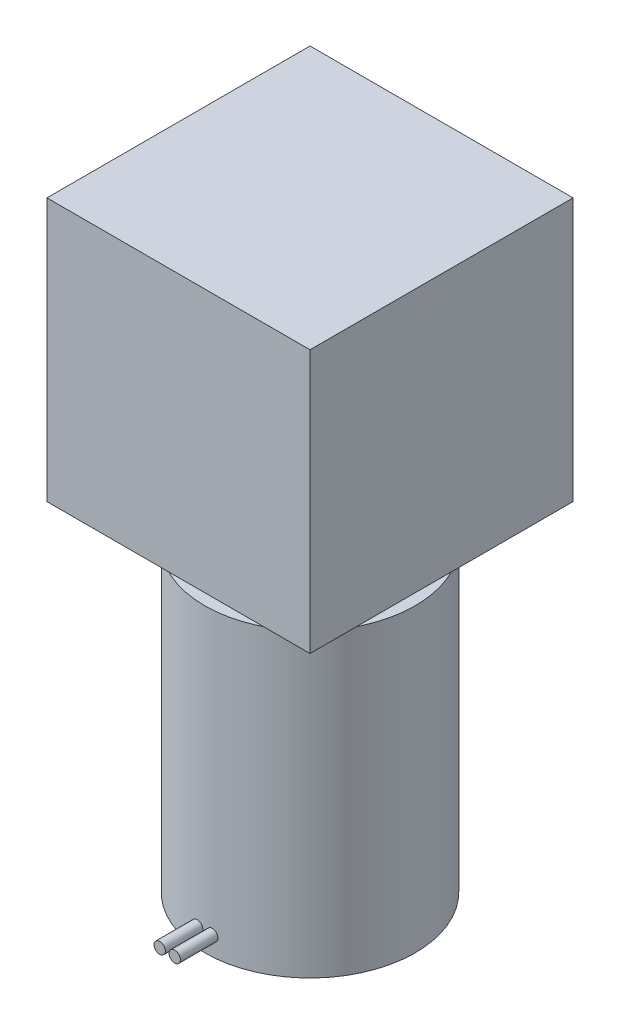
SolidWorks part; units mm, degrees
ref_plane "Front Plane" through (0, 0, 0) normal (0, 0, 1) x (1, 0, 0)
ref_plane "Top Plane" through (0, 0, 0) normal (0, 1, 0) x (1, 0, 0)
ref_plane "Right Plane" through (0, 0, 0) normal (1, 0, 0) x (0, 0, -1)
sketch "Sketch1" plane through (0, 0, 0) normal (0, 1, 0) x (1, 0, 0)
  circle A0 centre (0, 0) radius 28
  dimension "D1" = 56
extrude "Boss-Extrude1" add sketch "Sketch1" along normal blind 80
sketch "Sketch3" plane through (0, 80, 0) normal (0, 1, 0) x (1, 0, 0)
  circle A0 centre (0, 0) radius 22.5
  dimension "D1" = 45
extrude "Boss-Extrude2" add sketch "Sketch3" along normal blind 10
sketch "Sketch4" plane through (0, 90, 0) normal (0, 1, 0) x (1, 0, 0)
  line L1 (-35, 35) -> (35, 35)
  line L2 (-35, 35) -> (-35, -35)
  line L3 (-35, -35) -> (35, -35)
  line L4 (35, 35) -> (35, -35)
  line L5 (-35, 35) -> (35, -35) construction
  line L6 (-35, -35) -> (35, 35) construction
  point P0 (0, 0)
  dimension "D1" = 70
  dimension "D2" = 70
extrude "Boss-Extrude3" add sketch "Sketch4" along normal blind 70
sketch "Sketch5" plane through (-35, 0, 0) normal (-1, 0, 0) x (0, 0, 1)
  circle A0 centre (0, 125) radius 5.5
  circle A1 centre (0, 152) radius 2.5
  circle A2 centre (19.0919, 144.0919) radius 2.5
  circle A3 centre (27, 125) radius 2.5
  circle A4 centre (19.0919, 105.9081) radius 2.5
  circle A5 centre (0, 98) radius 2.5
  circle A6 centre (-19.0919, 105.9081) radius 2.5
  circle A7 centre (-27, 125) radius 2.5
  circle A8 centre (-19.0919, 144.0919) radius 2.5
  point P20 (0, 125)
  dimension "D1" = 11
  dimension "D2" = 5
  dimension "D3" = 27
  dimension "D4" = 8
extrude "Cut-Extrude1" cut sketch "Sketch5" against normal blind 20
ref_plane "Plane2" through (0, 0, 28) normal (0, 0, 1) x (1, 0, 0)
sketch "Sketch6" plane through (0, 0, 28) normal (0, 0, 1) x (1, 0, 0)
  circle A0 centre (-2, 5.1539) radius 1.5
  circle A1 centre (2, 5.1539) radius 1.5
  dimension "D1" = 3
  dimension "D2" = 3
  dimension "D3" = 4
  dimension "D4" = 2
extrude "Boss-Extrude4" add sketch "Sketch6" along normal blind 10 separate body
sketch "Sketch7" plane through (-35, 0, 0) normal (-1, 0, 0) x (0, 0, 1)
  line L1 (-6.5, 126.5) -> (-4.5, 126.5)
  line L2 (-6.5, 126.5) -> (-6.5, 123.5)
  line L3 (-6.5, 123.5) -> (-4.5, 123.5)
  line L4 (-4.5, 126.5) -> (-4.5, 123.5)
  line L5 (-6.5, 126.5) -> (-4.5, 123.5) construction
  line L6 (-6.5, 123.5) -> (-4.5, 126.5) construction
  circle A0 centre (0, 125) radius 5.5 construction
  circle A1 centre (0, 125) radius 5.5 construction
  point P0 (-5.5, 125)
  dimension "D2" = 3
  dimension "D1" = 2
extrude "Cut-Extrude2" cut sketch "Sketch7" against normal blind 20
sketch "Sketch8" plane through (-35, 0, 0) normal (-1, 0, 0) x (0, 0, 1)
  circle A0 centre (0, 125) radius 18.4154
  circle A1 centre (0, 125) radius 7.7343
extrude "Cut-Extrude4" cut sketch "Sketch8" against normal blind 10
